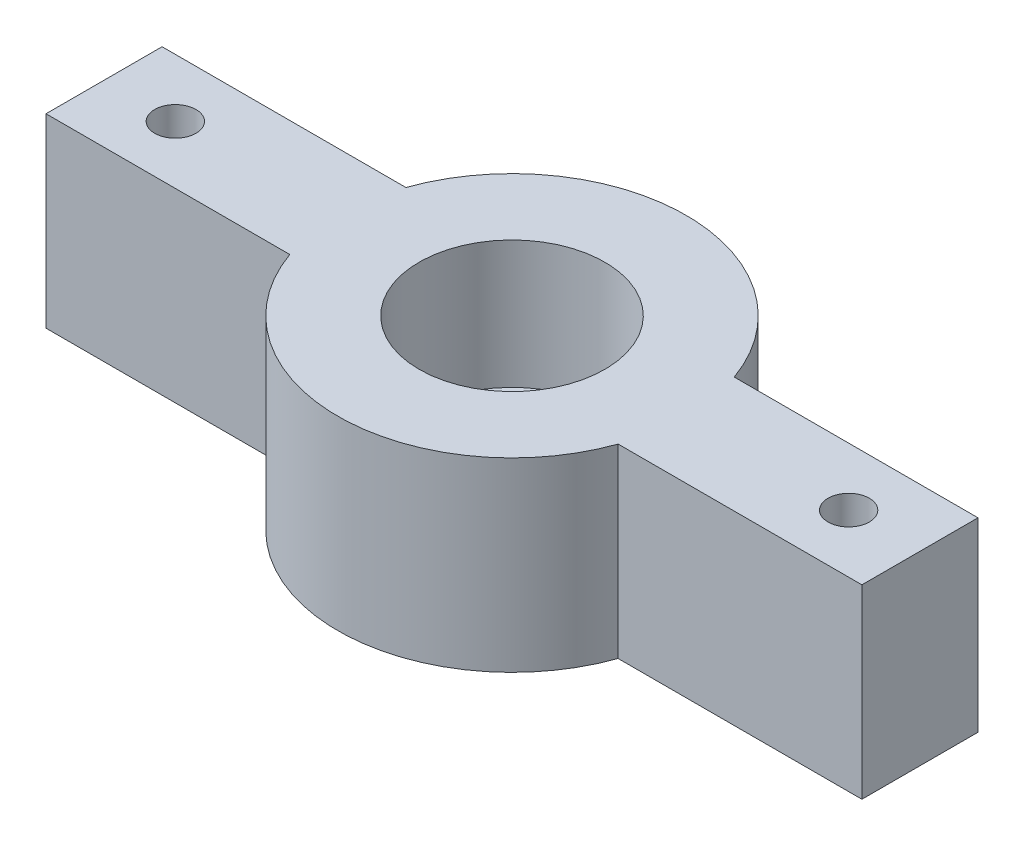
SolidWorks part; units mm, degrees
ref_plane "Front Plane" through (0, 0, 0) normal (0, 0, 1) x (1, 0, 0)
ref_plane "Top Plane" through (0, 0, 0) normal (0, 1, 0) x (1, 0, 0)
ref_plane "Right Plane" through (0, 0, 0) normal (1, 0, 0) x (0, 0, -1)
sketch "Sketch1" plane through (0, 0, 0) normal (0, 1, 0) x (1, 0, 0)
  line L0 (-7.0711, 2.5) -> (-17.5711, 2.5)
  line L1 (-17.5711, 2.5) -> (-17.5711, -2.5)
  line L3 (-17.5711, -2.5) -> (-7.0711, -2.5)
  line L4 (-26.3789, 0) -> (26.3789, 0) construction
  line L5 (-7.0711, 2.5) -> (-18.0711, 2.5) construction
  line L6 (7.0711, -2.5) -> (26.3789, -2.5) construction
  line L7 (0, 0) -> (0, 16.7972) construction
  line L8 (7.0711, 2.5) -> (17.5711, 2.5)
  line L9 (17.5711, 2.5) -> (17.5711, -2.5)
  line L10 (17.5711, -2.5) -> (7.0711, -2.5)
  arc A0 (-7.0711, -2.5) -> (7.0711, -2.5) centre (0, 0) ccw
  arc A1 (7.0711, 2.5) -> (-7.0711, 2.5) centre (0, 0) ccw
  circle A3 centre (0, 0) radius 1.875
  circle A5 centre (-14.5, 0) radius 0.889
  circle A6 centre (14.5, 0) radius 0.889
  dimension "D3" = 15
  dimension "D5" = 3.75
extrude "Boss-Extrude1" add sketch "Sketch1" along normal blind 8
sketch "Sketch2" plane through (0, 8, 0) normal (0, 1, 0) x (1, 0, 0)
  circle A0 centre (0, 0) radius 4
  dimension "D1" = 8
extrude "Cut-Extrude1" cut sketch "Sketch2" against normal blind 5.5
